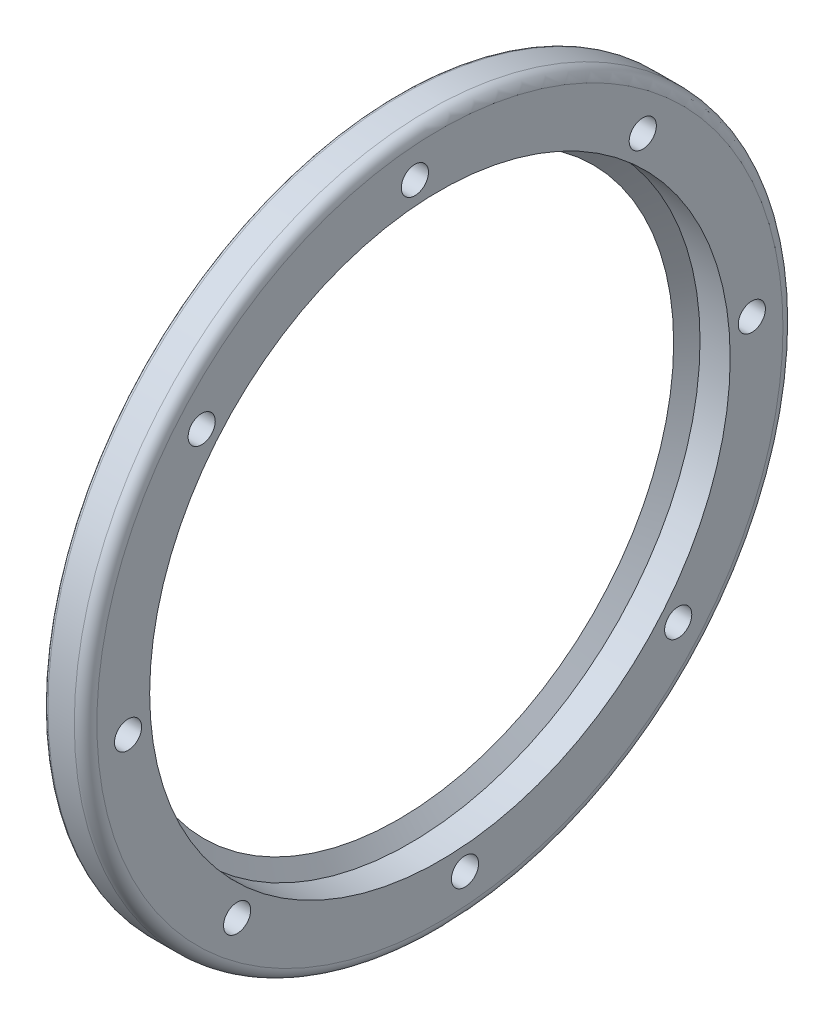
SolidWorks part; units mm, degrees
ref_plane "Front Plane" through (0, 0, 0) normal (0, 0, 1) x (1, 0, 0)
ref_plane "Top Plane" through (0, 0, 0) normal (0, 1, 0) x (1, 0, 0)
ref_plane "Right Plane" through (0, 0, 0) normal (1, 0, 0) x (0, 0, -1)
sketch "Sketch1" plane through (0, 0, 0) normal (0, 0, 1) x (1, 0, 0)
  line L0 (0, 0) -> (5.5, 0)
  line L1 (5.5, -6) -> (0, -6)
  line L2 (0, 0) -> (0, -6)
  line L3 (5.5, 0) -> (5.5, -6)
  line L4 (0, -6) -> (0, -8)
  line L5 (0, -6) -> (1.5, -6)
  line L6 (0, -8) -> (1.5, -6)
  line L7 (0, -8) -> (0, -44.5) construction
  line L8 (-1000, -44.5) -> (49000, -44.5)
  line L9 (5.5, -6) -> (5.5, -5.9999)
  line L10 (0, 0) -> (0, 2.5)
  line L11 (5.5, 2.5) -> (5.5, -0.5)
  line L12 (5.5, 2.5) -> (0, 2.5)
  dimension "D1" = 5.5
  dimension "D2" = 6
  dimension "D3" = 2
  dimension "D4" = 36.5
  dimension "D5" = 2.5
revolve "Revolve1" add sketch "Sketch1" angle 360 about L8
sketch "Sketch4" plane through (5.5, 0, 0) normal (-1, 0, 0) x (0, 0, 1)
  circle A0 centre (26.901, -76.1004) radius 4.7046 construction
hole_wizard "M3 Clearance Hole3" positions "Sketch5" profile "Sketch6" hole size "M3" standard "ANSI Metric"
sketch "Sketch5" plane through (5.5, 0, 0) normal (1, 0, 0) x (0, 0, -1)
  point P0 (-26.901, -76.1004)
sketch "Sketch6" plane through (5.5, -76.1004, 26.901) normal (0, 1, 0) x (0, 0, -1)
  line L0 (0, 0) -> (0, 6.5815)
  line L1 (0, 6.5815) -> (1.8, 5.5)
  line L2 (1.8, 5.5) -> (1.8, 0)
  line L5 (1.8, 0) -> (0, 0)
  line L10 (0, 6.5815) -> (-1.8, 5.5) construction
  line L11 (0, -6.35) -> (0, 107.95) construction
  dimension "Hole Dia." = 3.6
  dimension "Hole Depth" = 5.5
  dimension "Drill Angle" = 118
pattern_circular "CirPattern1" count 8 every 45 about axis through (0, -44.5, 0) along (1, 0, 0) of "M3 Clearance Hole3"
fillet "Fillet1" radius 1.5 1 edges at (5.5, -44.5, 47)
fillet "Fillet2" radius 0.5 1 edges at (0, -44.5, 47)
